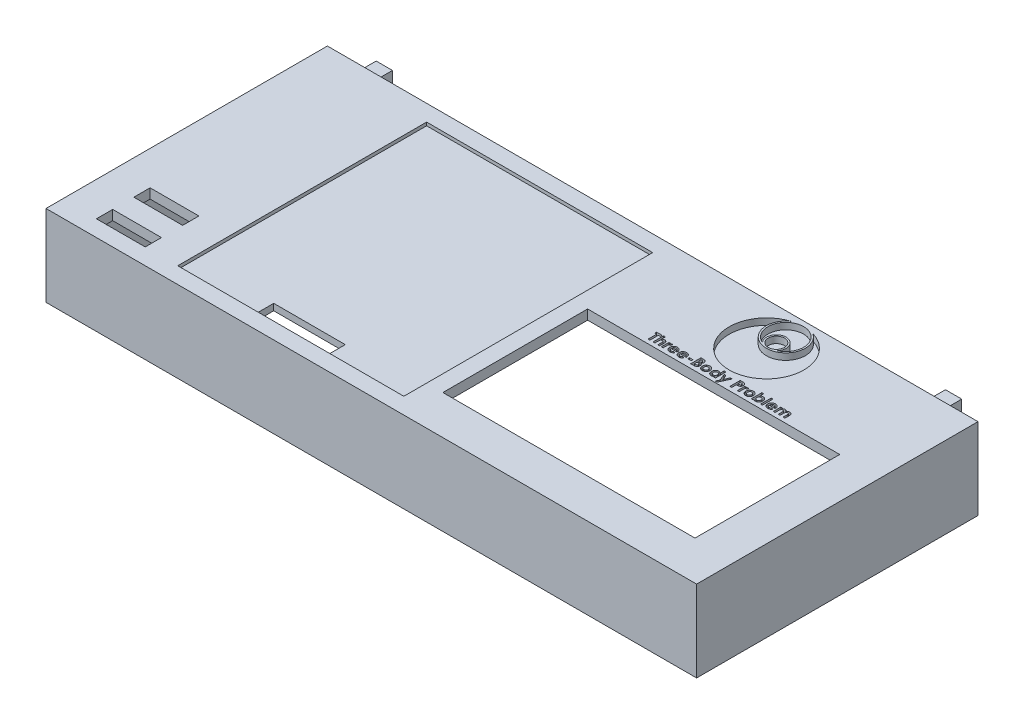
SolidWorks part; units mm, degrees
ref_plane "Front Plane" through (0, 0, 0) normal (0, 0, 1) x (1, 0, 0)
ref_plane "Top Plane" through (0, 0, 0) normal (0, 1, 0) x (1, 0, 0)
ref_plane "Right Plane" through (0, 0, 0) normal (1, 0, 0) x (0, 0, -1)
sketch "Sketch1" plane through (0, 0, 0) normal (0, 1, 0) x (1, 0, 0)
  line L1 (100, -43.25) -> (-100, -43.25)
  line L2 (100, -43.25) -> (100, 43.25)
  line L3 (100, 43.25) -> (-100, 43.25)
  line L4 (-100, -43.25) -> (-100, 43.25)
  line L5 (100, -43.25) -> (-100, 43.25) construction
  line L6 (100, 43.25) -> (-100, -43.25) construction
  point P0 (0, 0)
  dimension "D1" = 200
  dimension "D2" = 86.5
extrude "Boss-Extrude1" add sketch "Sketch1" along normal mid plane 25
shell "Shell1" thickness 3
sketch "Sketch2" plane through (0, 12.5, 0) normal (0, 1, 0) x (1, 0, 0)
  line L0 (-100, -43.25) -> (100, -43.25) construction
  line L1 (-64.5, 38.25) -> (5, 38.25)
  line L2 (-64.5, 38.25) -> (-64.5, -38.25)
  line L3 (-64.5, -38.25) -> (5, -38.25)
  line L4 (5, 38.25) -> (5, -38.25)
  line L5 (-64.5, 38.25) -> (5, -38.25) construction
  line L6 (-64.5, -38.25) -> (5, 38.25) construction
  point P0 (-29.75, 0)
  dimension "D1" = 76.5
  dimension "D2" = 69.5
  dimension "D3" = 5
  dimension "D4" = 5
sketch "Sketch3" plane through (0, 12.5, 0) normal (0, 1, 0) x (1, 0, 0)
  line L0 (100, -43.25) -> (100, 43.25) construction
  line L1 (10, 13.25) -> (87.5, 13.25)
  line L2 (10, 13.25) -> (10, -31.25)
  line L3 (10, -31.25) -> (87.5, -31.25)
  line L4 (87.5, 13.25) -> (87.5, -31.25)
  line L5 (10, 13.25) -> (87.5, -31.25) construction
  line L6 (10, -31.25) -> (87.5, 13.25) construction
  line L8 (100, 43.25) -> (-100, 43.25) construction
  point P0 (48.75, -9)
  dimension "D1" = 77.5
  dimension "D2" = 44.5
  dimension "D3" = 12.5
  dimension "D4" = 30
sketch "Sketch5" plane through (0, 12.5, 0) normal (0, 1, 0) x (1, 0, 0)
  line L0 (-89.5, -38.25) -> (-74.5, -38.25)
  line L1 (-89.5, -26.75) -> (-74.5, -26.75)
  line L2 (-89.5, -26.75) -> (-89.5, -21.75)
  line L3 (-89.5, -21.75) -> (-74.5, -21.75)
  line L4 (-74.5, -26.75) -> (-74.5, -21.75)
  line L5 (-89.5, -38.25) -> (-89.5, -33.25)
  line L6 (-89.5, -33.25) -> (-74.5, -33.25)
  line L7 (-74.5, -38.25) -> (-74.5, -33.25)
  line L9 (-64.5, 38.25) -> (-64.5, -38.25) construction
  line L10 (-100, -43.25) -> (100, -43.25) construction
  dimension "D1" = 5
  dimension "D2" = 15
  dimension "D3" = 6.5
  dimension "D4" = 10
  dimension "D5" = 15
  dimension "D6" = 5
  dimension "D7" = 5
extrude "Cut-Extrude1" cut sketch "Sketch5" against normal blind 30
extrude "Cut-Extrude2" cut sketch "Sketch2" against normal blind 1
sketch "Sketch6" plane through (0, 11.5, 0) normal (0, 1, 0) x (1, 0, 0)
  line L0 (-64.5, 38.25) -> (-64.5, -38.25) construction
  line L1 (-40.75, -32.5) -> (-18.75, -32.5)
  line L2 (-40.75, -32.5) -> (-40.75, -37.5)
  line L3 (-40.75, -37.5) -> (-18.75, -37.5)
  line L4 (-18.75, -32.5) -> (-18.75, -37.5)
  line L7 (-64.5, -38.25) -> (5, -38.25) construction
  dimension "D1" = 22
  dimension "D2" = 5
  dimension "D3" = 23.75
  dimension "D4" = 0.75
extrude "Cut-Extrude3" cut sketch "Sketch6" against normal through all
extrude "Cut-Extrude4" cut sketch "Sketch3" against normal through all
sketch "Sketch9" plane through (0, 0, -43.25) normal (0, 0, -1) x (-1, 0, 0)
  line L0 (-100, 12.5) -> (100, 12.5) construction
  line L1 (-90, 11) -> (-85, 11)
  line L2 (-90, 11) -> (-90, 3.5)
  line L3 (-90, 3.5) -> (-85, 3.5)
  line L4 (-85, 11) -> (-85, 3.5)
  line L5 (-100, 12.5) -> (-100, -12.5) construction
  line L6 (47.575, 0) -> (-47.575, 0) construction
  line L7 (-90, -3.5) -> (-85, -3.5)
  line L8 (-85, -11) -> (-85, -3.5)
  line L9 (-90, -11) -> (-85, -11)
  line L10 (-90, -11) -> (-90, -3.5)
  line L11 (0, 13.75) -> (0, -13.75) construction
  line L12 (90, -11) -> (90, -3.5)
  line L13 (90, -11) -> (85, -11)
  line L14 (85, -11) -> (85, -3.5)
  line L15 (90, -3.5) -> (85, -3.5)
  line L16 (90, 3.5) -> (85, 3.5)
  line L17 (85, 11) -> (85, 3.5)
  line L18 (90, 11) -> (85, 11)
  line L19 (90, 11) -> (90, 3.5)
  dimension "D1" = 1.5
  dimension "D2" = 10
  dimension "D3" = 7.5
  dimension "D4" = 5
extrude "Boss-Extrude2" add sketch "Sketch9" along normal blind 5
sketch "Sketch10" plane through (0, 0, -43.25) normal (0, 0, -1) x (-1, 0, 0)
  line L0 (0, 13.75) -> (0, -13.75) construction
  line L1 (37.5, -12.5) -> (-37.5, -12.5)
  line L2 (37.5, -12.5) -> (37.5, 5)
  line L3 (37.5, 5) -> (-37.5, 5)
  line L4 (-37.5, -12.5) -> (-37.5, 5)
  line L5 (37.5, -12.5) -> (-37.5, 5) construction
  line L6 (37.5, 5) -> (-37.5, -12.5) construction
  line L7 (-100, -12.5) -> (100, -12.5) construction
  point P0 (0, -3.75)
  dimension "D1" = 17.5
  dimension "D2" = 75
extrude "Cut-Extrude5" cut sketch "Sketch10" against normal up to surface (3 mm away) up to face at (0, -1.5, -40.25)
sketch "Sketch13" plane through (-100, 0, 0) normal (-1, 0, 0) x (0, 0, 1)
  line L0 (50.325, 0) -> (-50.325, 0) construction
  line L1 (-43.25, 12.5) -> (-43.25, -12.5) construction
  point P0 (-28.25, 0)
  dimension "D1" = 15
hole_wizard "Ø1.0mm Dowel Hole2" positions "Sketch13" profile "Sketch14" hole size "Ø1.0" standard "ANSI Metric"
sketch "Sketch14" plane through (-100, 0, -28.25) normal (0, 1, 0) x (0, 0, 1)
  line L0 (0, 0) -> (0, 6.3798)
  line L1 (0, 6.3798) -> (5.625, 3)
  line L2 (5.625, 3) -> (5.625, 0)
  line L5 (5.625, 0) -> (0, 0)
  line L10 (0, 6.3798) -> (-5.625, 3) construction
  line L11 (0, -6.35) -> (0, 107.95) construction
  dimension "Hole Dia." = 11.25
  dimension "Hole Depth" = 3
  dimension "Drill Angle" = 118
sketch "Sketch15" plane through (-100, 0, 0) normal (-1, 0, 0) x (0, 0, 1)
  line L0 (50.325, 0) -> (-50.325, 0) construction
  line L1 (43.25, 12.5) -> (43.25, -12.5) construction
  point P0 (-6.75, 0)
  dimension "D1" = 50
hole_wizard "Ø1.0mm Dowel Hole3" positions "Sketch15" profile "Sketch16" hole size "Ø1.0" standard "ANSI Metric"
sketch "Sketch16" plane through (-100, 0, -6.75) normal (0, 1, 0) x (0, 0, 1)
  line L0 (0, 0) -> (0, 5.4786)
  line L1 (0, 5.4786) -> (4.125, 3)
  line L2 (4.125, 3) -> (4.125, 0)
  line L5 (4.125, 0) -> (0, 0)
  line L10 (0, 5.4786) -> (-4.125, 3) construction
  line L11 (0, -6.35) -> (0, 107.95) construction
  dimension "Hole Dia." = 8.25
  dimension "Hole Depth" = 3
  dimension "Drill Angle" = 118
sketch "Sketch17" plane through (0, 12.5, 0) normal (0, 1, 0) x (1, 0, 0)
  line L0 (137.9926, 328.1986) -> (557.9926, 328.1986) construction
  line L1 (100, 43.25) -> (-100, 43.25) construction
  line L2 (87.5, -31.25) -> (87.5, 13.25) construction
  circle A0 centre (48, 33.25) radius 2.5
  circle A1 centre (47.9184, 36.2489) radius 5.5
  circle A2 centre (48, 30.2494) radius 11.5
  circle A3 centre (48, 33.25) radius 3
  circle A4 centre (47.9184, 36.2489) radius 6
  circle A5 centre (48, 30.2494) radius 12
  dimension "D1" = 5
  dimension "D2" = 11
  dimension "D3" = 23
  dimension "D4" = 10
  dimension "D5" = 39.5
  dimension "D6" = 2.9989
  dimension "D7" = 0.5
  dimension "D8" = 0.5
  dimension "D9" = 0.5
extrude "Cut-Extrude7" cut sketch "Sketch17" against normal blind 2 contours A0 | A3 A1 | A4 A2
sketch "Sketch18" plane through (0, 12.5, 0) normal (0, 1, 0) x (1, 0, 0)
  line L0 (26.5, 14.5) -> (69.5, 14.5) construction
  line L3 (87.5, 13.25) -> (10, 13.25) construction
  arc A0 (44.5655, 41.2246) -> (51.1349, 41.3139) centre (48, 30.2494) ccw construction
  arc A1 (44.5655, 41.2246) -> (51.1349, 41.3139) centre (48, 30.2494) ccw construction
  text T0 "<b>Three-Body Problem</b>" font "Century Gothic" height in points 12
  dimension "D1" = 21.5
  dimension "D2" = 21.5
  dimension "D3" = 1.25
extrude "Cut-Extrude8" cut sketch "Sketch18" against normal blind 2
